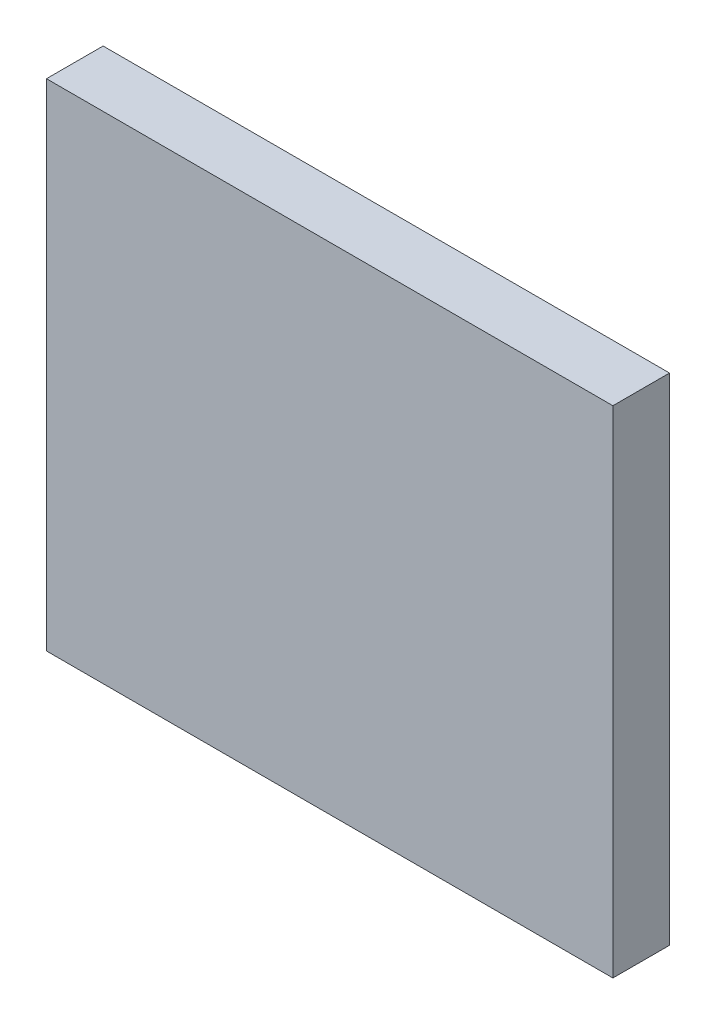
SolidWorks part; units mm, degrees
ref_plane "Front Plane" through (0, 0, 0) normal (0, 0, 1) x (1, 0, 0)
ref_plane "Top Plane" through (0, 0, 0) normal (0, 1, 0) x (1, 0, 0)
ref_plane "Right Plane" through (0, 0, 0) normal (1, 0, 0) x (0, 0, -1)
sketch "Sketch1" plane through (0, 0, 0) normal (0, 0, 1) x (1, 0, 0)
  line L1 (0, 0) -> (40, 0)
  line L2 (0, 0) -> (0, 35)
  line L3 (0, 35) -> (40, 35)
  line L4 (40, 0) -> (40, 35)
  dimension "D1" = 40
  dimension "D2" = 35
extrude "Profile" add sketch "Sketch1" along normal blind 4
equation "\"Profile_Depth\"= 4mm"
equation "\"D1@Profile\" = \"Profile_Depth\""
equation "\"Profile_Sketch_1\"= 40mm"
equation "\"D1@Sketch1\" = \"Profile_Sketch_1\""
equation "\"Profile_Sketch_2\"= 35mm"
equation "\"D2@Sketch1\" = \"Profile_Sketch_2\""
equation "\"EnvelopeWidth\"= 40mm"
equation "\"EnvelopeHeight\"= 35mm"
